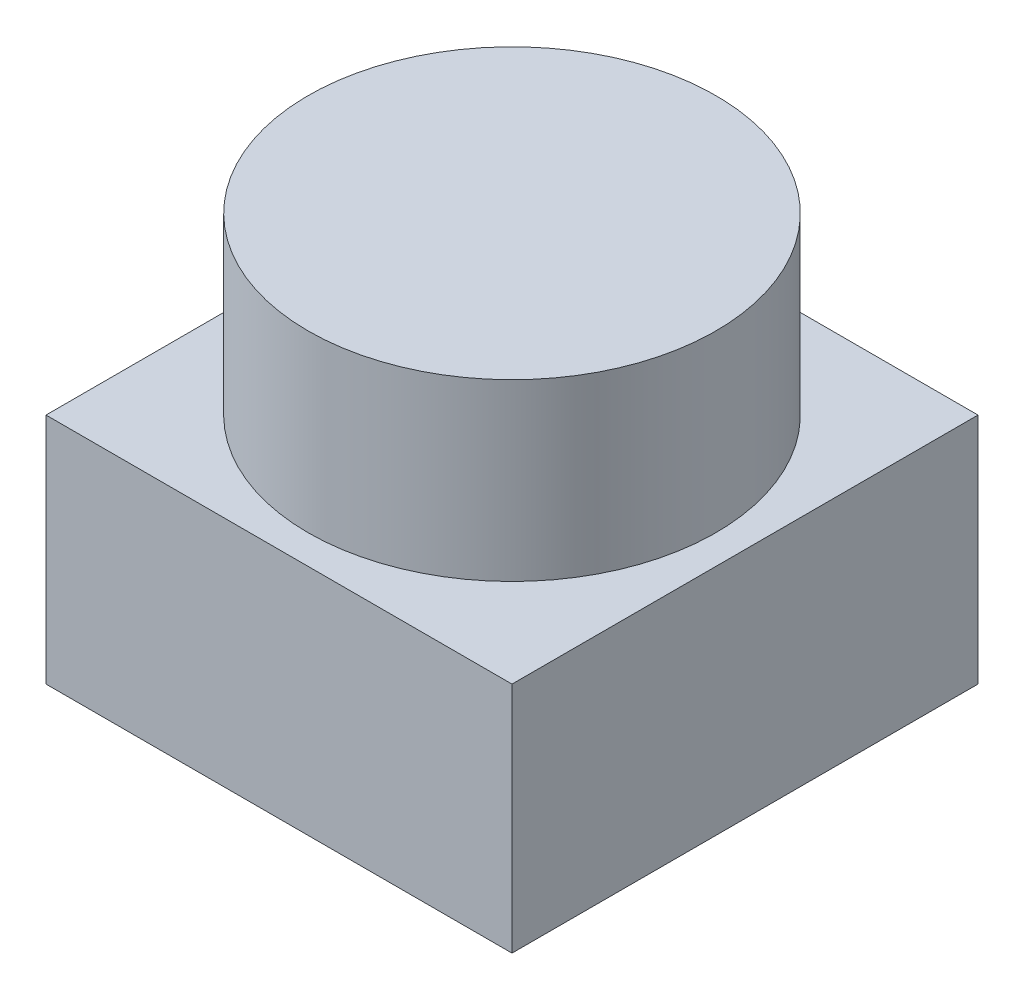
SolidWorks part; units mm, degrees
ref_plane "前视基准面" through (0, 0, 0) normal (0, 0, 1) x (1, 0, 0)
ref_plane "上视基准面" through (0, 0, 0) normal (0, 1, 0) x (1, 0, 0)
ref_plane "右视基准面" through (0, 0, 0) normal (1, 0, 0) x (0, 0, -1)
other "Configuration Table"
sketch "草图1" plane through (0, 0, 0) normal (0, 1, 0) x (1, 0, 0)
  line L1 (-17.9817, 22.2018) -> (22.0183, 22.2018)
  line L2 (-17.9817, 22.2018) -> (-17.9817, -17.7982)
  line L3 (-17.9817, -17.7982) -> (22.0183, -17.7982)
  line L4 (22.0183, 22.2018) -> (22.0183, -17.7982)
  dimension "D1" = 40
extrude "凸台-拉伸1" add sketch "草图1" along normal blind 20
sketch "草图2" plane through (0, 20, 0) normal (0, 1, 0) x (1, 0, 0)
  line L0 (-17.9817, 2.2018) -> (22.0183, 2.2018) construction
  line L1 (-17.9817, 22.2018) -> (-17.9817, -17.7982) construction
  line L2 (22.0183, -17.7982) -> (22.0183, 22.2018) construction
  line L3 (2.0183, 22.2018) -> (2.0183, -17.7982) construction
  line L4 (22.0183, 22.2018) -> (-17.9817, 22.2018) construction
  line L5 (-17.9817, -17.7982) -> (22.0183, -17.7982) construction
  circle A0 centre (2.0183, 2.2018) radius 17.5
  dimension "D1" = 35
extrude "凸台-拉伸2" add sketch "草图2" along normal blind 15
